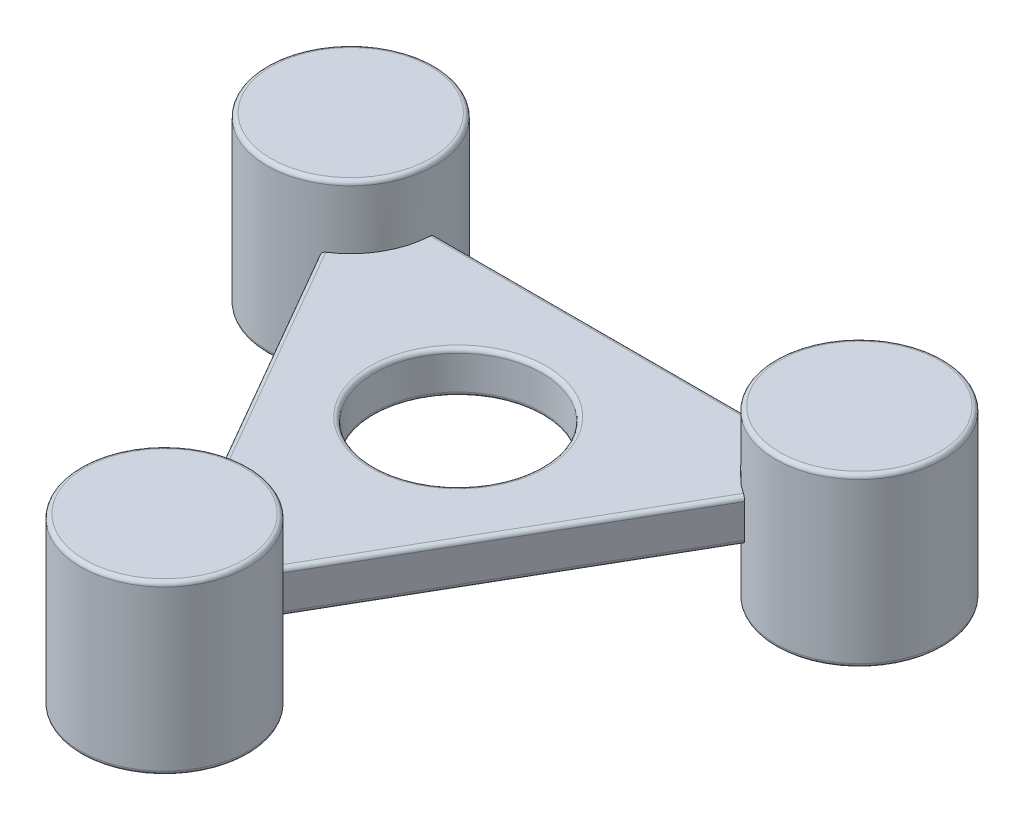
SolidWorks part; units mm, degrees
ref_plane "Alzado" through (0, 0, 0) normal (0, 0, 1) x (1, 0, 0)
ref_plane "Planta" through (0, 0, 0) normal (0, 1, 0) x (1, 0, 0)
ref_plane "Vista lateral" through (0, 0, 0) normal (1, 0, 0) x (0, 0, -1)
sketch "Croquis1" plane through (0, 0, 0) normal (0, 1, 0) x (1, 0, 0)
  line L0 (-0.9093, 0.525) -> (0.9093, 0.525) construction
  circle A0 centre (-0.9093, 0.525) radius 0.3
  circle A1 centre (0, 0) radius 1.05 construction
  circle A2 centre (0.9093, 0.525) radius 0.3
  circle A3 centre (0, -1.05) radius 0.3
  point P12 (0, 0)
  dimension "D2" = 0.6
  dimension "D3" = 2.1
  dimension "D1" = 3
extrude "Saliente-Extruir1" add sketch "Croquis1" along normal mid plane 0.6
sketch "Croquis2" plane through (0, 0, 0) normal (0, 1, 0) x (1, 0, 0)
  line L0 (-0.9093, 0.525) -> (0.9093, 0.525)
  line L1 (0.9093, 0.525) -> (0, -1.05)
  line L2 (0, -1.05) -> (-0.9093, 0.525)
extrude "Saliente-Extruir2" add sketch "Croquis2" along normal mid plane 0.15
fillet "Redondeo1" radius 0.015 6 edges at (0, -0.075, -0.525) (0.4547, -0.075, 0.2625) (-0.4547, -0.075, 0.2625) (0, 0.075, -0.525) (0.4547, 0.075, 0.2625) (-0.4547, 0.075, 0.2625)
fillet "Redondeo2" radius 0.015 6 edges at (0, -0.3, 1.35) (0, 0.3, 1.35) (-0.9093, 0.3, -0.225) (-0.9093, -0.3, -0.225) (0.9093, -0.3, -0.225) (0.9093, 0.3, -0.225)
sketch "Croquis3" plane through (0, 0.075, 0) normal (0, 1, 0) x (1, 0, 0)
  circle A0 centre (0, 0) radius 0.3
  dimension "D1" = 0.6
extrude "Cortar-Extruir1" cut sketch "Croquis3" against normal blind 1
fillet "Redondeo3" radius 0.015 2 edges at (0, -0.075, -0.3) (0, 0.075, 0.3)
sketch "Croquis7" plane through (0, 0.075, 0) normal (0, 1, 0) x (1, 0, 0)
  line L0 (-0.6047, -1.0473) -> (0.1098, -1.4598)
  line L1 (0.1098, -1.4598) -> (0.7145, -0.4125)
  line L2 (0, 0) -> (-0.6047, -1.0473)
  line L3 (0, 0) -> (0.7145, -0.4125)
  circle A0 centre (0, -1.05) radius 0.3 construction
  circle A1 centre (0.9093, 0.525) radius 0.3 construction
  circle A2 centre (0, -1.05) radius 0.3
  circle A3 centre (0.9093, 0.525) radius 0.3
  point P10 (0, 0)
